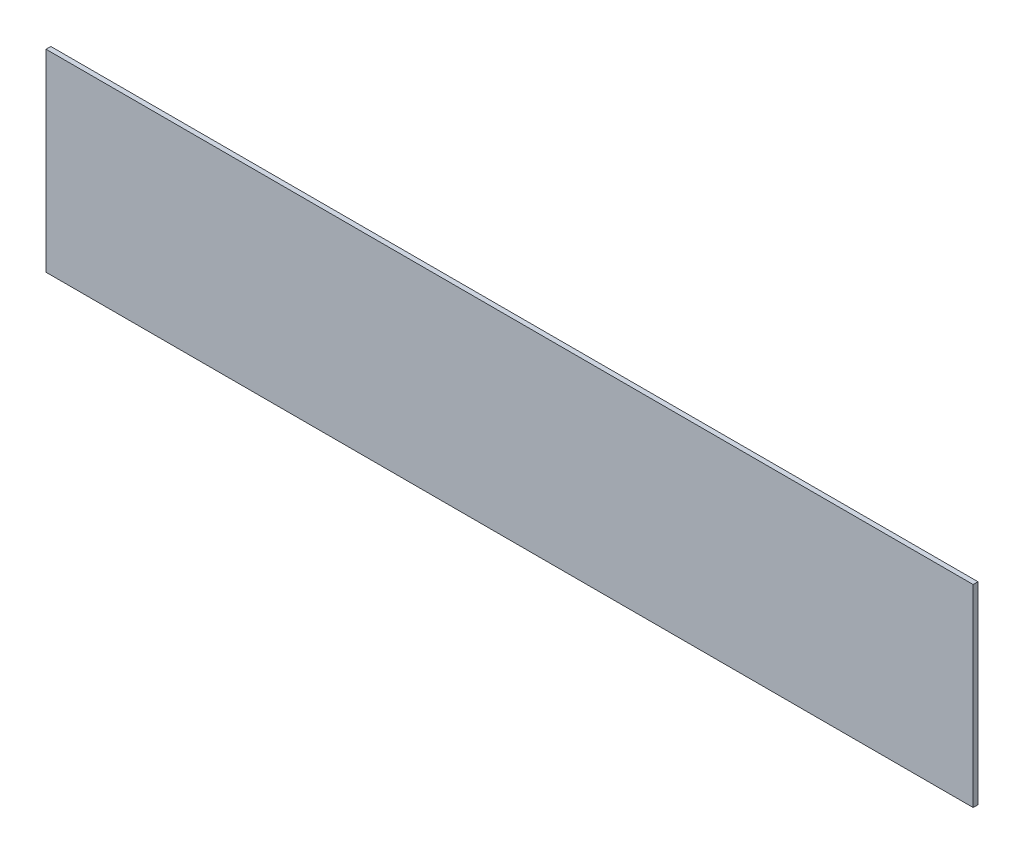
SolidWorks part; units mm, degrees
material "Pine"
ref_plane "Front Plane" through (0, 0, 0) normal (0, 0, 1) x (1, 0, 0)
ref_plane "Top Plane" through (0, 0, 0) normal (0, 1, 0) x (1, 0, 0)
ref_plane "Right Plane" through (0, 0, 0) normal (1, 0, 0) x (0, 0, -1)
sketch "Sketch1" plane through (0, 0, 0) normal (0, 0, 1) x (1, 0, 0)
  line L1 (0, 0) -> (2438.4, 0)
  line L2 (0, 0) -> (0, 508)
  line L3 (0, 508) -> (2438.4, 508)
  line L4 (2438.4, 0) -> (2438.4, 508)
  dimension "D1" = 2438.4
  dimension "D2" = 508
extrude "Boss-Extrude1" add sketch "Sketch1" along normal blind 12.7
